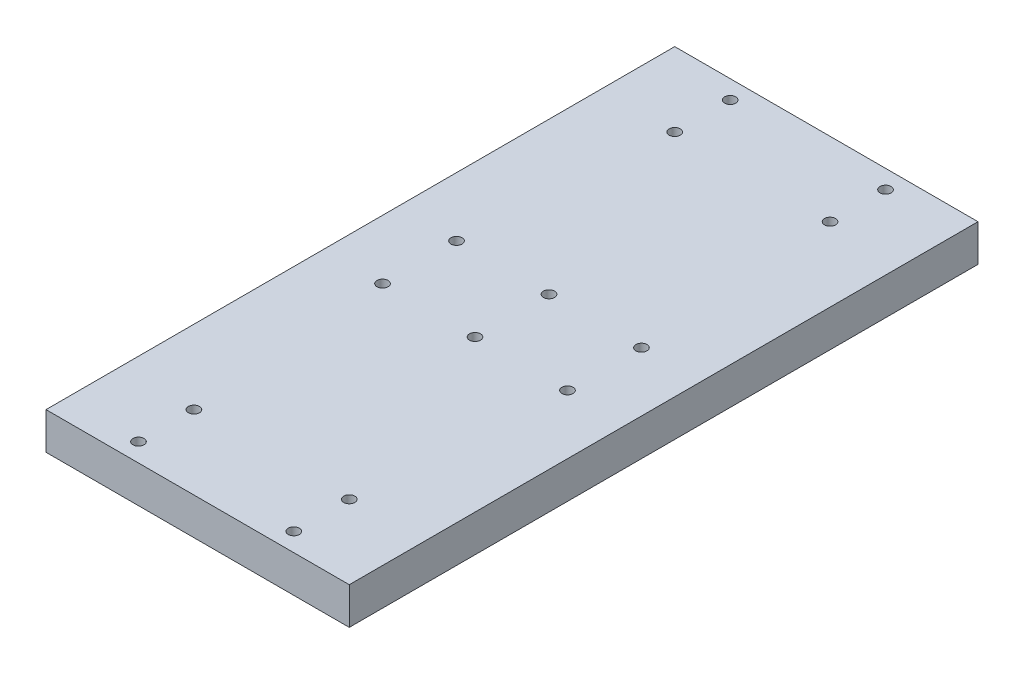
SolidWorks part; units mm, degrees
ref_plane "前视基准面" through (0, 0, 0) normal (0, 0, 1) x (1, 0, 0)
ref_plane "上视基准面" through (0, 0, 0) normal (0, 1, 0) x (1, 0, 0)
ref_plane "右视基准面" through (0, 0, 0) normal (1, 0, 0) x (0, 0, -1)
sketch "草图1" plane through (0, 0, 0) normal (0, 1, 0) x (1, 0, 0)
  line L1 (-41, 85) -> (41, 85)
  line L2 (-41, 85) -> (-41, -85)
  line L3 (-41, -85) -> (41, -85)
  line L4 (41, 85) -> (41, -85)
  line L5 (-41, 85) -> (41, -85) construction
  line L6 (-41, -85) -> (41, 85) construction
  point P0 (0, 0)
  dimension "D1" = 82
  dimension "D2" = 170
extrude "凸台-拉伸1" add sketch "草图1" along normal blind 10
sketch "草图2" plane through (0, 10, 0) normal (0, 1, 0) x (1, 0, 0)
  line L1 (-25, -10) -> (25, -10) construction
  line L2 (-25, -10) -> (-25, 10) construction
  line L3 (-25, 10) -> (25, 10) construction
  line L4 (25, -10) -> (25, 10) construction
  line L5 (-25, -10) -> (25, 10) construction
  line L6 (-25, 10) -> (25, -10) construction
  circle A0 centre (-25, 10) radius 1.5
  circle A1 centre (0, 10) radius 1.5
  circle A2 centre (25, 10) radius 1.5
  circle A3 centre (-25, -10) radius 1.5
  circle A4 centre (0, -10) radius 1.5
  circle A5 centre (25, -10) radius 1.5
  point P0 (0, 0)
  dimension "D3" = 3
  dimension "D4" = 3
  dimension "D5" = 3
  dimension "D6" = 3
  dimension "D7" = 3
  dimension "D8" = 3
  dimension "D1" = 50
  dimension "D2" = 20
extrude "切除-拉伸1" cut sketch "草图2" against normal through all
sketch "草图3" plane through (0, 0, 0) normal (0, -1, 0) x (1, 0, 0)
  line L0 (-21, 80) -> (-21, 65) construction
  line L1 (-41, 85) -> (41, 85) construction
  line L2 (-41, -85) -> (-41, 85) construction
  circle A0 centre (-21, 80) radius 1.5
  circle A1 centre (-21, 65) radius 1.5
  dimension "D1" = 3
  dimension "D2" = 3
  dimension "D3" = 15
  dimension "D4" = 5
  dimension "D5" = 20
extrude "切除-拉伸2" cut sketch "草图3" against normal blind 10
mirror "镜向1" about plane through (0, 0, 0) normal (0, 0, 1) of "切除-拉伸2"
mirror "镜向2" about plane through (0, 0, 0) normal (1, 0, 0) of "镜向1", "切除-拉伸2"
